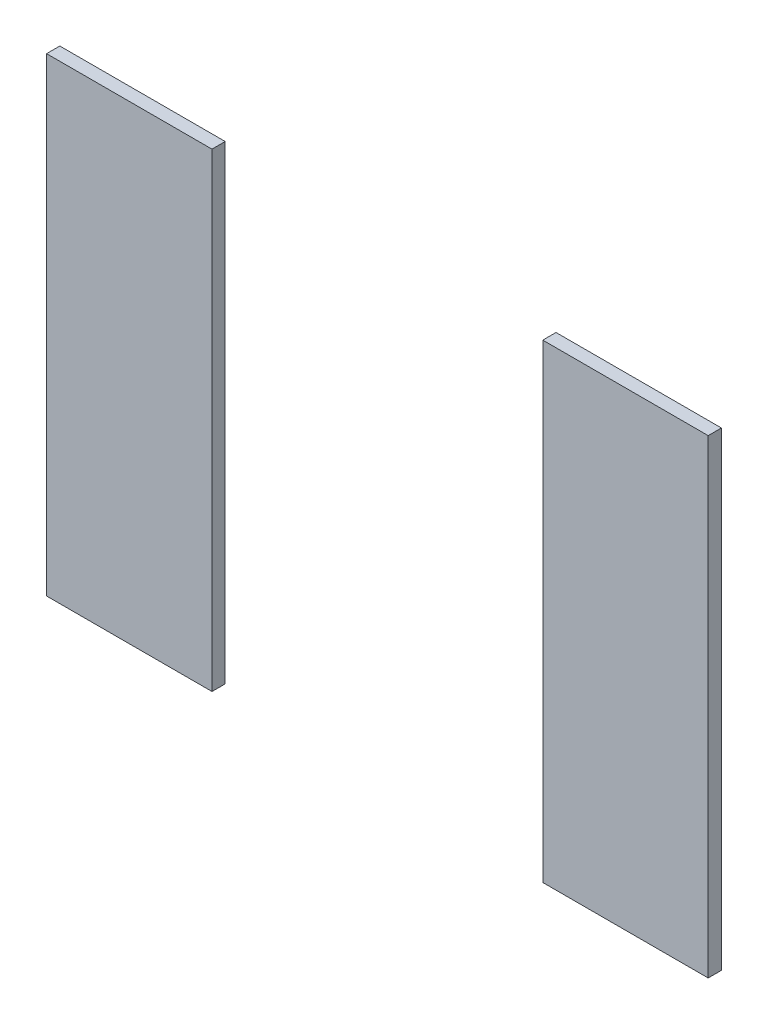
SolidWorks part; units mm, degrees
ref_plane "Front Plane" through (0, 0, 0) normal (0, 0, 1) x (1, 0, 0)
ref_plane "Top Plane" through (0, 0, 0) normal (0, 1, 0) x (1, 0, 0)
ref_plane "Right Plane" through (0, 0, 0) normal (1, 0, 0) x (0, 0, -1)
sketch "Sketch2" plane through (0, 0, 0) normal (0, 0, 1) x (1, 0, 0)
  line L0 (-500, 0) -> (500, 0)
  line L1 (-500, 0) -> (-500, -810)
  line L2 (500, 0) -> (500, -810)
  line L3 (-500, -810) -> (500, -810)
  line L4 (-250, 0) -> (-250, -810)
  line L5 (250, -810) -> (250, 0)
  line L6 (500, -243.561) -> (250, -243.561) construction
  line L7 (-500, -243.561) -> (-250, -243.561) construction
  line L8 (-500, -710) -> (500, -710)
  line L9 (340.1466, -710) -> (340.1466, -810) construction
  point P2 (0, 0)
  dimension "D1" = 250
  dimension "D2" = 810
  dimension "D3" = 1000
  dimension "D4" = 100
extrude "Boss-Extrude1" add sketch "Sketch2" along normal mid plane 20 contours L4 L0 L1 L3 | L5 L3 L2 L0
